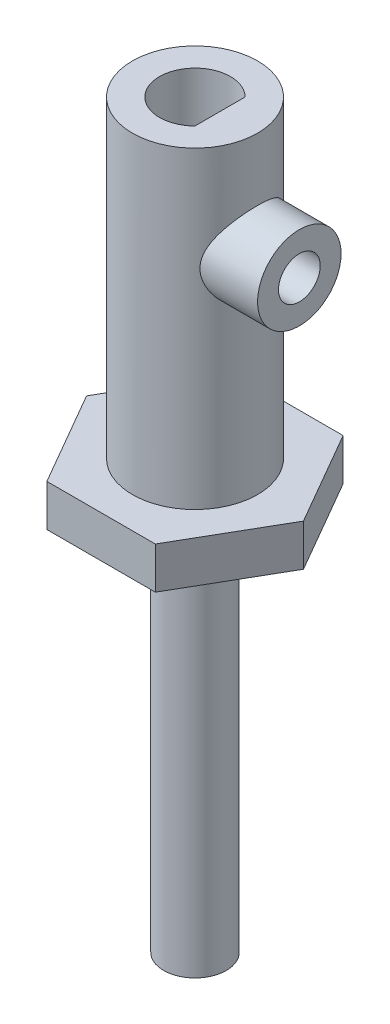
SolidWorks part; units mm, degrees
ref_plane "Front Plane" through (0, 0, 0) normal (0, 0, 1) x (1, 0, 0)
ref_plane "Top Plane" through (0, 0, 0) normal (0, 1, 0) x (1, 0, 0)
ref_plane "Right Plane" through (0, 0, 0) normal (1, 0, 0) x (0, 0, -1)
sketch "Sketch1" plane through (0, 0, 0) normal (0, 1, 0) x (1, 0, 0)
  circle A0 centre (0, 0) radius 3
  dimension "D1" = 6
extrude "Boss-Extrude1" add sketch "Sketch1" along normal blind 17
ref_plane "Plane1" through (0, 17, 0) normal (0, 1, 0) x (1, 0, 0)
ref_point "Point1"
sketch "Sketch2" plane through (0, 17, 0) normal (0, 1, 0) x (1, 0, 0)
  line L0 (1.2, 1.2042) -> (1.2, -1.2042)
  arc A0 (1.2, 1.2042) -> (1.2, -1.2042) centre (0, 0) ccw
  dimension "D1" = 3.4
  dimension "D2" = 1.2
extrude "Cut-Extrude3" cut sketch "Sketch2" against normal blind 10.2
ref_plane "Plane2" through (0, 0, 0) normal (0, -1, 0) x (-1, 0, 0)
sketch "Sketch3" plane through (0, 0, 0) normal (0, -1, 0) x (-1, 0, 0)
  line L1 (5.1962, 0) -> (2.5981, 4.5)
  line L2 (2.5981, 4.5) -> (-2.5981, 4.5)
  line L3 (-2.5981, 4.5) -> (-5.1962, 0)
  line L4 (-5.1962, 0) -> (-2.5981, -4.5)
  line L5 (-2.5981, -4.5) -> (2.5981, -4.5)
  line L6 (2.5981, -4.5) -> (5.1962, 0)
  circle A0 centre (0, 0) radius 4.5 construction
extrude "Boss-Extrude2" add sketch "Sketch3" against normal blind 2
sketch "Sketch4" plane through (0, 0, 0) normal (0, -1, 0) x (-1, 0, 0)
  circle A0 centre (0, 0) radius 1.5
  dimension "D1" = 3
extrude "Boss-Extrude3" add sketch "Sketch4" along normal blind 18.5
ref_plane "Plane3" through (3, 0, 0) normal (1, 0, 0) x (0, 0, -1)
sketch "Sketch6" plane through (3, 0, 0) normal (1, 0, 0) x (0, 0, -1)
  line L0 (3.3, 17) -> (-3.3, 17) construction
  circle A0 centre (0, 12) radius 1
  circle A1 centre (0, 12) radius 2
  dimension "D2" = 2
  dimension "D3" = 4
  dimension "D1" = 5
extrude "Boss-Extrude4" add sketch "Sketch6" along normal blind 2 and the other way blind 1
ref_point "Point3"
sketch "Sketch7" plane through (3, 0, 0) normal (1, 0, 0) x (0, 0, -1)
  circle A0 centre (0, 12) radius 1.1
extrude "Cut-Extrude4" cut sketch "Sketch7" against normal blind 3
